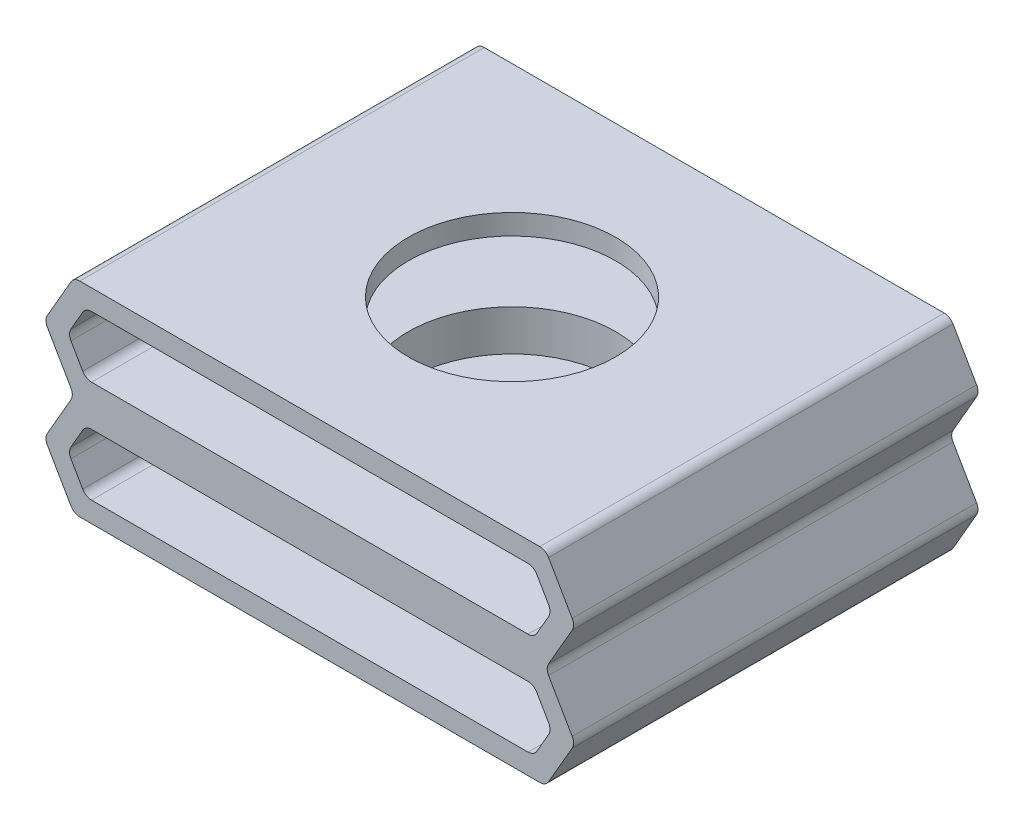
SolidWorks part; units mm, degrees
ref_plane "Front Plane" through (0, 0, 0) normal (0, 0, 1) x (1, 0, 0)
ref_plane "Top Plane" through (0, 0, 0) normal (0, 1, 0) x (1, 0, 0)
ref_plane "Right Plane" through (0, 0, 0) normal (1, 0, 0) x (0, 0, -1)
sketch "Sketch5" plane through (0, 0, 0) normal (0, 0, 1) x (1, 0, 0)
  line L66 (1.4434, 2.5) -> (-1.4434, 2.5)
  line L67 (-1.4434, 2.5) -> (-2.8868, 0)
  line L68 (-2.8868, 0) -> (-1.4434, -2.5)
  line L72 (4.3301, 2.5) -> (1.4434, 2.5)
  line L78 (7.2169, 2.5) -> (4.3301, 2.5)
  line L84 (10.1036, 2.5) -> (7.2169, 2.5)
  line L90 (12.9904, 2.5) -> (10.1036, 2.5)
  line L96 (15.8771, 2.5) -> (12.9904, 2.5)
  line L102 (18.7639, 2.5) -> (15.8771, 2.5)
  line L107 (23.094, 0) -> (21.6506, 2.5)
  line L108 (21.6506, 2.5) -> (18.7639, 2.5)
  line L112 (21.6506, -2.5) -> (23.094, 0)
  line L115 (-1.4434, -2.5) -> (-2.8868, -5)
  line L116 (-2.8868, -5) -> (-1.4434, -7.5)
  line L117 (-1.4434, -7.5) -> (1.4434, -7.5)
  line L123 (1.4434, -7.5) -> (4.3301, -7.5)
  line L129 (4.3301, -7.5) -> (7.2169, -7.5)
  line L135 (7.2169, -7.5) -> (10.1036, -7.5)
  line L141 (10.1036, -7.5) -> (12.9904, -7.5)
  line L147 (12.9904, -7.5) -> (15.8771, -7.5)
  line L153 (15.8771, -7.5) -> (18.7639, -7.5)
  line L155 (23.094, -5) -> (21.6506, -2.5)
  line L159 (18.7639, -7.5) -> (21.6506, -7.5)
  line L160 (21.6506, -7.5) -> (23.094, -5)
  line L162 (2.8868, 0) -> (2.1651, 1.25) [skipped]
  line L163 (0.866, 1.5) -> (-0.866, 1.5)
  line L164 (1.4434, -2.5) -> (1.6368, -2.1651) [skipped]
  line L165 (0, -2.5) -> (1.4434, -2.5) [skipped]
  line L166 (1.4434, -2.5) -> (0, -2.5) [skipped]
  line L167 (-0.866, 1.5) -> (-1.7321, 0)
  line L168 (-1.7321, 0) -> (-0.866, -1.5)
  line L169 (2.1651, -6.25) -> (2.8868, -5) [skipped]
  line L170 (2.1651, -3.75) -> (1.6368, -2.8349) [skipped]
  line L171 (-0.866, -1.5) -> (0.866, -1.5)
  line L173 (21.9393, 0) -> (21.0733, 1.5)
  line L174 (21.0733, 1.5) -> (19.3412, 1.5)
  line L177 (19.3412, -1.5) -> (21.0733, -1.5)
  line L178 (21.0733, -1.5) -> (21.9393, 0)
  line L179 (0.866, -1.5) -> (19.3412, -1.5)
  line L181 (0.866, 1.5) -> (19.3412, 1.5)
  line L184 (0.866, -3.5) -> (-0.866, -3.5)
  line L185 (-0.866, -3.5) -> (-1.7321, -5)
  line L186 (-1.7321, -5) -> (-0.866, -6.5)
  line L187 (-0.866, -6.5) -> (0.866, -6.5)
  line L189 (21.9393, -5) -> (21.0733, -3.5)
  line L190 (21.0733, -3.5) -> (19.3412, -3.5)
  line L193 (19.3412, -6.5) -> (21.0733, -6.5)
  line L194 (21.0733, -6.5) -> (21.9393, -5)
  line L195 (0.866, -6.5) -> (19.3412, -6.5)
  line L197 (0.866, -3.5) -> (19.3412, -3.5)
  line L213 (18.0422, -3.75) -> (17.3205, -5) [skipped]
  line L214 (18.5705, -7.1651) -> (18.7639, -7.5) [skipped]
  line L217 (21.6506, -2.5) -> (20.2073, -2.5) [skipped]
  line L218 (20.2073, -2.5) -> (21.6506, -2.5) [skipped]
  line L219 (17.3205, 0) -> (18.0422, -1.25) [skipped]
  line L220 (18.5705, 2.1651) -> (18.0422, 1.25) [skipped]
  line L221 (1.7321, 0) -> (1.299, 0.75) [skipped]
  line L222 (0.866, -1.5) -> (1.299, -0.75) [skipped]
  line L223 (18.9082, 0.75) -> (18.4752, 0) [skipped]
  line L224 (18.9082, -0.75) -> (19.3412, -1.5) [skipped]
  line L225 (1.7321, -5) -> (1.299, -4.25) [skipped]
  line L226 (0.866, -6.5) -> (1.299, -5.75) [skipped]
  line L227 (18.9082, -4.25) -> (18.4752, -5) [skipped]
  line L228 (18.9082, -5.75) -> (19.3412, -6.5) [skipped]
  circle A0 centre (0, 0) radius 2.5 construction
  circle A1 centre (0, 0) radius 1.5 construction
  circle A2 centre (20.2073, 0) radius 1.5 construction
  circle A3 centre (0, -5) radius 1.5 construction
  circle A4 centre (20.2073, -5) radius 1.5 construction
  circle A7 centre (20.2073, 0) radius 2.5 construction
  circle A8 centre (0, -5) radius 2.5 construction
  circle A15 centre (20.2073, -5) radius 2.5 construction
extrude "Boss-Extrude5" add sketch "Sketch5" along normal blind 19.8 contours L181 L163 L167 L168 L171 L179 L177 L178 L173 L174 | L197 L184 L185 L186 L187 L195 L193 L194 L189 L190 | L102 L96 L90 L84 L78 L72 L66 L67 L68 L115 L116 L117 L123 L129 L135 L141 L147 L153 L159 L160 L155 L112 L107 L108
sketch "Sketch6" plane through (0, -7.5, 0) normal (0, -1, 0) x (1, 0, 0)
  line L3 (-1.4434, 19.8) -> (-1.4434, 0) construction
  line L4 (21.6506, 19.8) -> (-1.4434, 19.8) construction
  circle A1 centre (10.1036, 9.9) radius 5.075
  dimension "D1" = 10.15
  dimension "D2" = 11.547
  dimension "D3" = 9.9
extrude "Cut-Extrude1" cut sketch "Sketch6" against normal blind 10 contours A1
fillet "Fillet2" radius 0.5 22 edges at (21.0733, -6.5, 9.9) (21.9393, -5, 9.9) (21.0733, -3.5, 9.9) (21.0733, -1.5, 9.9) (21.9393, 0, 9.9) (21.0733, 1.5, 9.9) (-0.866, -6.5, 9.9) (-0.866, -1.5, 9.9) (-0.866, -3.5, 9.9) (-1.7321, -5, 9.9) (-1.7321, 0, 9.9) (-0.866, 1.5, 9.9) (21.6506, 2.5, 9.9) (23.094, 0, 9.9) (21.6506, -2.5, 9.9) (23.094, -5, 9.9) (21.6506, -7.5, 9.9) (-1.4434, 2.5, 9.9) (-2.8868, 0, 9.9) (-1.4434, -2.5, 9.9) (-2.8868, -5, 9.9) (-1.4434, -7.5, 9.9)
